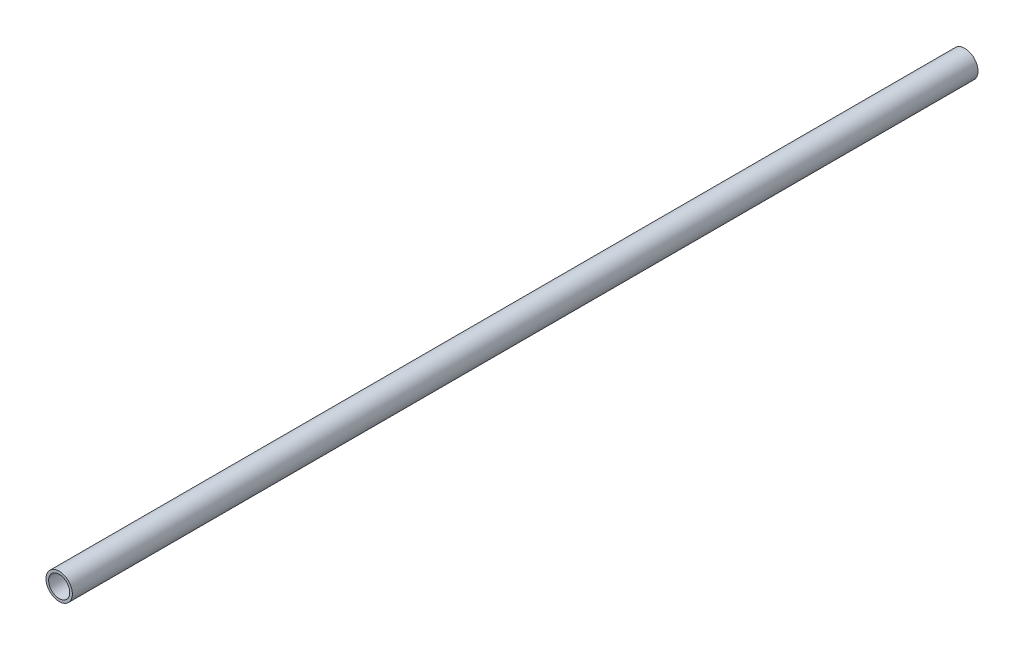
SolidWorks part; units mm, degrees
material "Aluminium 6060 T6"
ref_plane "Front Plane" through (0, 0, 0) normal (0, 0, 1) x (1, 0, 0)
ref_plane "Top Plane" through (0, 0, 0) normal (0, 1, 0) x (1, 0, 0)
ref_plane "Right Plane" through (0, 0, 0) normal (1, 0, 0) x (0, 0, -1)
sketch "Sketch1" plane through (0, 0, 0) normal (0, 0, 1) x (1, 0, 0)
  circle A0 centre (0, 0) radius 4
  dimension "D1" = 8
extrude "Extrude-Thin1" add sketch "Sketch1" along normal blind 343 thin
